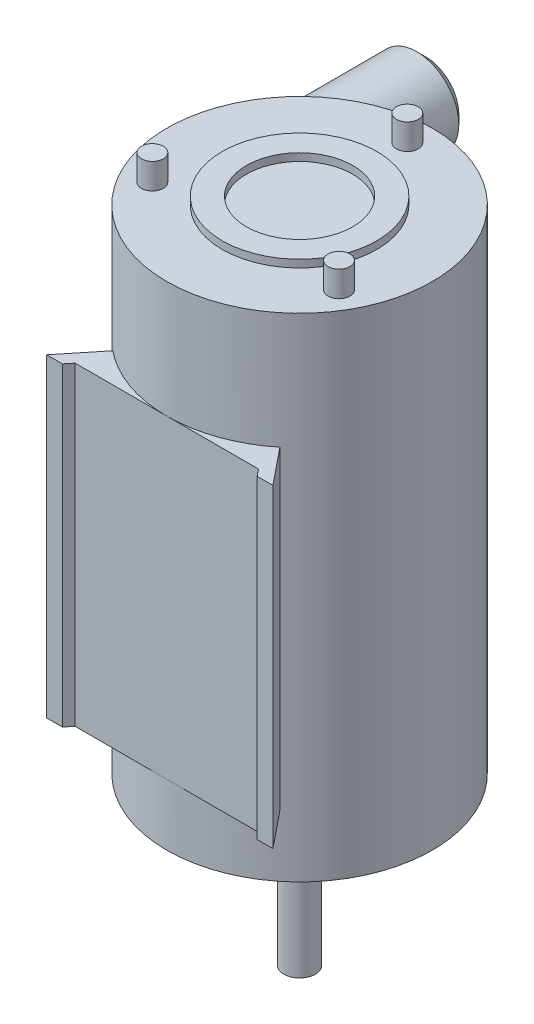
SolidWorks part; units mm, degrees
material "1060 Alloy"
ref_plane "Front Plane" through (0, 0, 0) normal (0, 0, 1) x (1, 0, 0)
ref_plane "Top Plane" through (0, 0, 0) normal (0, 1, 0) x (1, 0, 0)
ref_plane "Right Plane" through (0, 0, 0) normal (1, 0, 0) x (0, 0, -1)
sketch "Sketch1" plane through (0, 0, 0) normal (0, 1, 0) x (1, 0, 0)
  circle A0 centre (0, 0) radius 11.5824
  dimension "D1" = 23.1648
extrude "Boss-Extrude1" add sketch "Sketch1" along normal blind 42.9514
sketch "Sketch2" plane through (0, 42.9514, 0) normal (0, 1, 0) x (1, 0, 0)
  circle A0 centre (0, 0) radius 6.7437
  circle A1 centre (0, 0) radius 4.6355
  dimension "D1" = 13.4874
  dimension "D2" = 9.271
extrude "Boss-Extrude2" add sketch "Sketch2" along normal blind 0.6604
sketch "Sketch3" plane through (0, 42.9514, 0) normal (0, 1, 0) x (1, 0, 0)
  circle A0 centre (0, 9.398) radius 0.9525
  circle A1 centre (0, 0) radius 9.398
  dimension "D1" = 1.905
  dimension "D2" = 18.796
extrude "Boss-Extrude3" add sketch "Sketch3" along normal blind 2.2352 contours A1 A0 | A0 A1
pattern_circular "CirPattern1" count 3 over 360 about axis through (0, 0, 0) along (0, 1, 0) of "Boss-Extrude3"
sketch "Sketch4" plane through (0, 0, 0) normal (0, 0, 1) x (1, 0, 0)
  line L0 (-11.5824, 42.9514) -> (-11.5824, 0) construction
  line L1 (11.5824, 42.9514) -> (-11.5824, 42.9514) construction
  circle A0 centre (-7.9121, 37.8333) radius 3.6703
  circle A1 centre (-7.9121, 37.8333) radius 2.4511
  dimension "D1" = 7.3406
  dimension "D2" = 4.9022
  dimension "D3" = 5.1181
extrude "Boss-Extrude4" add sketch "Sketch4" against normal blind 18.923
chamfer "Chamfer1" distance 0.7937 angle 45 1 edges at (-4.2418, 37.8333, -18.923)
sketch "Sketch5" plane through (0, 0, 0) normal (0, -1, 0) x (1, 0, 0)
  circle A0 centre (4.318, 4.318) radius 1.3652
  dimension "D1" = 2.7305
  dimension "D2" = 4.318
  dimension "D3" = 4.318
extrude "Boss-Extrude5" add sketch "Sketch5" along normal blind 10.16
ref_plane "Plane1" through (0, 32.7914, 0) normal (0, 1, 0) x (1, 0, 0)
sketch "Sketch7" plane through (0, 32.7914, 0) normal (0, 1, 0) x (1, 0, 0)
  line L0 (-8.001, -11.5824) -> (8.001, -11.5824)
  line L1 (8.001, -11.5824) -> (8.4943, -12.192)
  line L2 (8.4943, -12.192) -> (9.8659, -12.192)
  line L3 (9.8659, -12.192) -> (0, 0)
  line L4 (0, 0) -> (0, -11.5824)
  line L5 (-8.4943, -12.192) -> (-9.8659, -12.192)
  line L6 (-8.001, -11.5824) -> (-8.4943, -12.192)
  line L7 (-9.8659, -12.192) -> (0, 0)
  circle A0 centre (0, 0) radius 11.5824 construction
  dimension "D2" = 0.6096
  dimension "D1" = 8.001
  dimension "D4" = 1.3716
extrude "Boss-Extrude6" add sketch "Sketch7" against normal blind 27.432 contours L3 L4 L0 L1 L2 | L7 L5 L6 L0 L4
